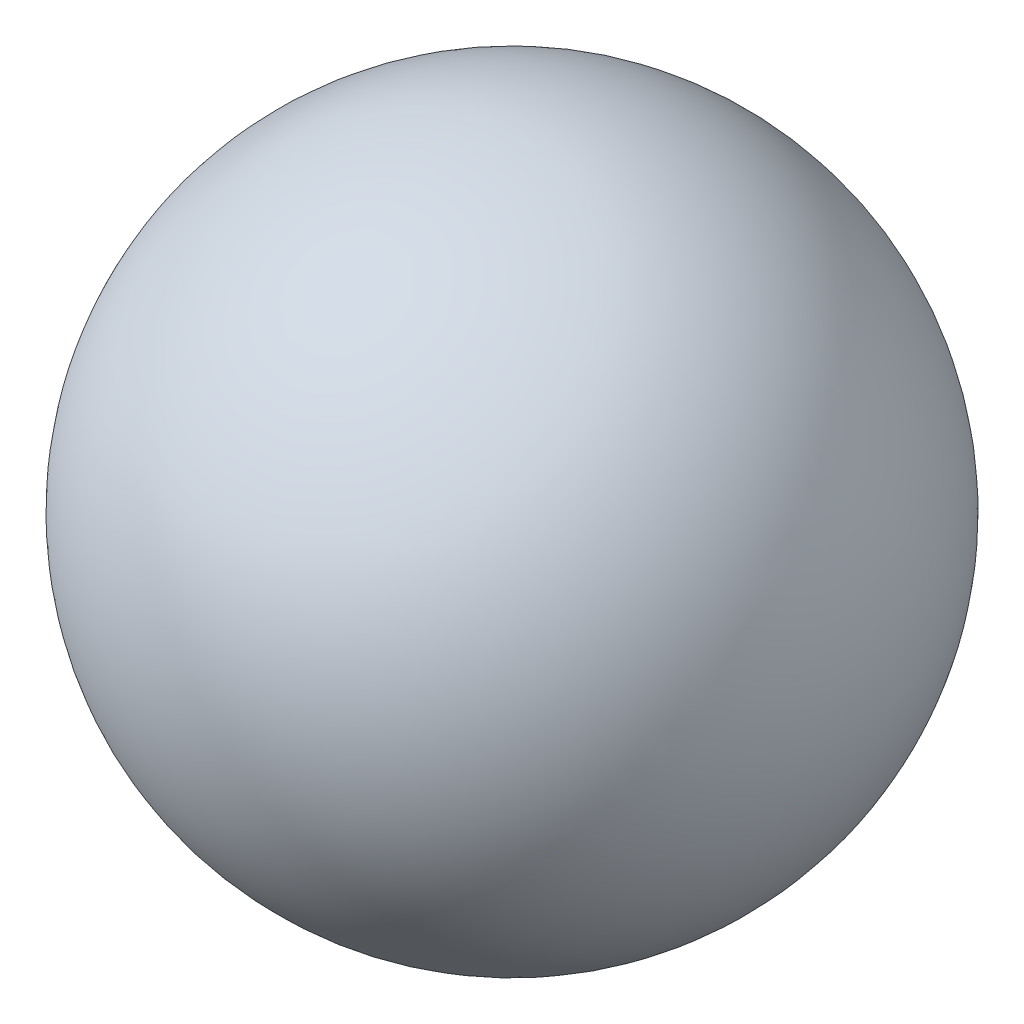
SolidWorks part; units mm, degrees
ref_plane "Front Plane" through (0, 0, 0) normal (0, 0, 1) x (1, 0, 0)
ref_plane "Top Plane" through (0, 0, 0) normal (0, 1, 0) x (1, 0, 0)
ref_plane "Right Plane" through (0, 0, 0) normal (1, 0, 0) x (0, 0, -1)
sketch "Sketch1" plane through (0, 0, 0) normal (0, 1, 0) x (1, 0, 0)
  line L0 (0, 0) -> (42.672, 0)
  arc A0 (0, 0) -> (42.672, 0) centre (21.336, 0) ccw
  point P3 (21.336, 0)
  point P5 (21.336, -6.0198)
  point P6 (0, 0)
  point P7 (0, 0)
  point P8 (21.336, -6.0198)
  point P9 (21.336, -6.0198)
  point P10 (0, 0)
  point P11 (21.336, -6.0198)
  point P12 (21.336, -6.0198)
  point P13 (0, 0)
  point P14 (21.336, 0)
  dimension "D1" = 42.672
revolve "Revolve1" add sketch "Sketch1" angle 360 about L0
